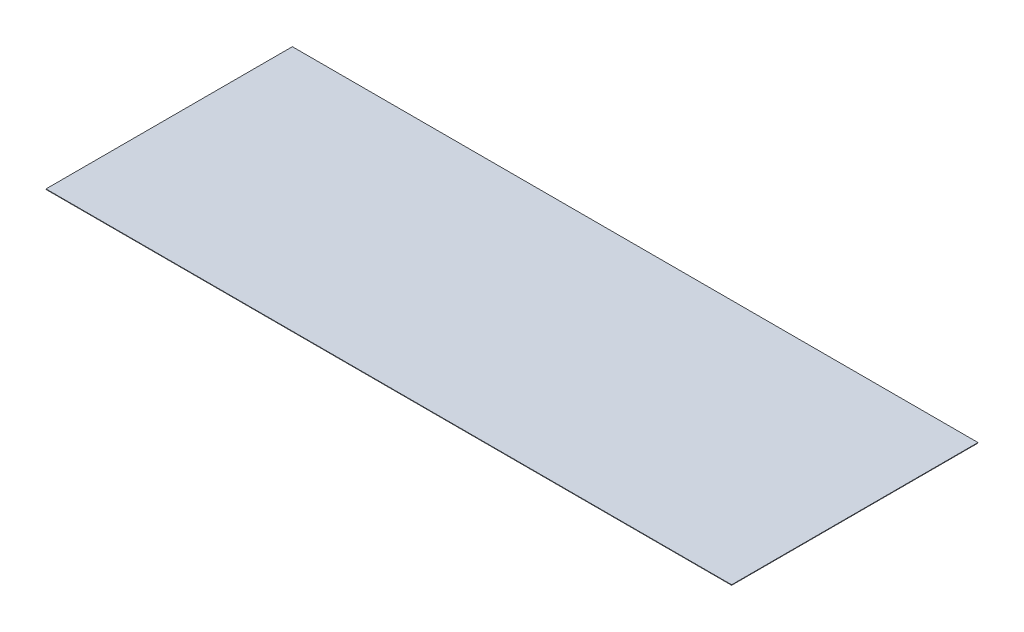
SolidWorks part; units mm, degrees
ref_plane "Front Plane" through (0, 0, 0) normal (0, 0, 1) x (1, 0, 0)
ref_plane "Top Plane" through (0, 0, 0) normal (0, 1, 0) x (1, 0, 0)
ref_plane "Right Plane" through (0, 0, 0) normal (1, 0, 0) x (0, 0, -1)
sketch "Sketch1" plane through (0, 0, 0) normal (0, 1, 0) x (1, 0, 0)
  line L1 (56.5, -20.3) -> (-56.5, -20.3)
  line L2 (56.5, -20.3) -> (56.5, 20.3)
  line L3 (56.5, 20.3) -> (-56.5, 20.3)
  line L4 (-56.5, -20.3) -> (-56.5, 20.3)
  line L5 (56.5, -20.3) -> (-56.5, 20.3) construction
  line L6 (56.5, 20.3) -> (-56.5, -20.3) construction
  point P0 (0, 0)
  dimension "D1" = 113
  dimension "D2" = 40.6
extrude "Boss-Extrude1" add sketch "Sketch1" along normal blind 0.08
